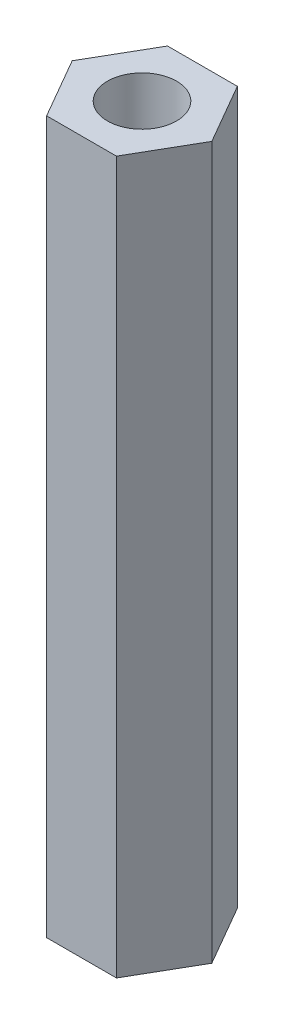
SolidWorks part; units mm, degrees
ref_plane "Front Plane" through (0, 0, 0) normal (0, 0, 1) x (1, 0, 0)
ref_plane "Top Plane" through (0, 0, 0) normal (0, 1, 0) x (1, 0, 0)
ref_plane "Right Plane" through (0, 0, 0) normal (1, 0, 0) x (0, 0, -1)
sketch "Sketch1" plane through (0, 0, 0) normal (0, 1, 0) x (1, 0, 0)
  line L1 (-2.0207, 3.5) -> (-4.0415, 0)
  line L2 (-4.0415, 0) -> (-2.0207, -3.5)
  line L3 (-2.0207, -3.5) -> (2.0207, -3.5)
  line L4 (2.0207, -3.5) -> (4.0415, 0)
  line L5 (4.0415, 0) -> (2.0207, 3.5)
  line L6 (2.0207, 3.5) -> (-2.0207, 3.5)
  circle A0 centre (0, 0) radius 2
  circle A1 centre (0, 0) radius 3.5 construction
  dimension "D1" = 4
  dimension "D2" = 7
extrude "Boss-Extrude1" add sketch "Sketch1" along normal blind 41.2
